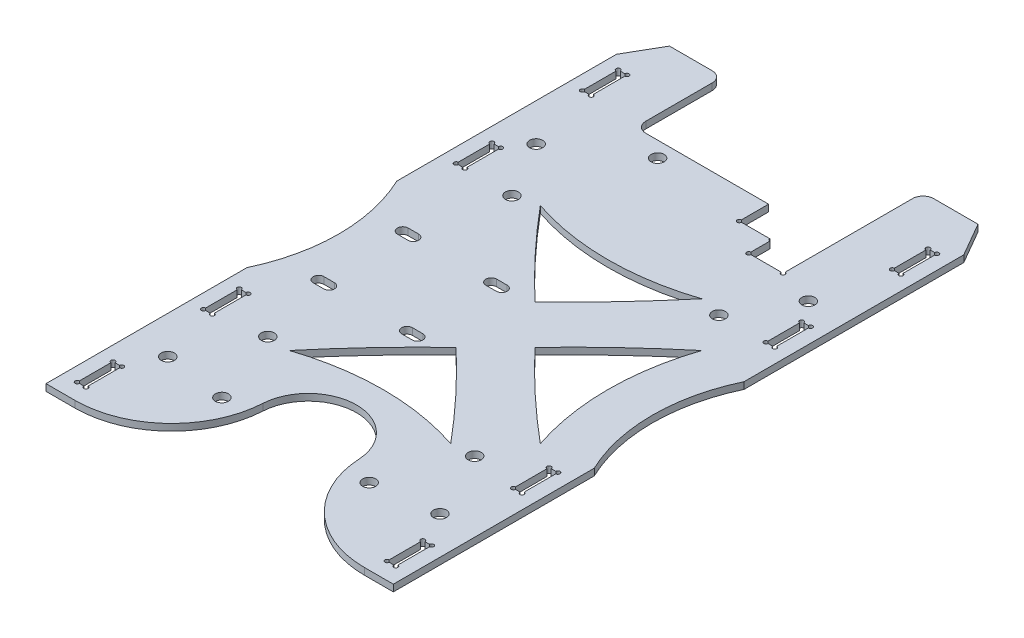
SolidWorks part; units mm, degrees
ref_plane "Front Plane" through (0, 0, 0) normal (0, 0, 1) x (1, 0, 0)
ref_plane "Top Plane" through (0, 0, 0) normal (0, 1, 0) x (1, 0, 0)
ref_plane "Right Plane" through (0, 0, 0) normal (1, 0, 0) x (0, 0, -1)
sketch "草图3" plane through (0, 0, 0) normal (0, 1, 0) x (1, 0, 0)
  line L0 (-126.4995, 10.5223) -> (116.8967, 10.5223) construction
  line L5 (15.4, 76.2723) -> (23.6, 76.2723)
  line L6 (15.4, 60.7723) -> (15.4, 76.2723)
  line L19 (15.4, 60.7723) -> (23.6, 60.7723)
  line L20 (30.4719, 92.0132) -> (48.4165, 101.8402)
  line L21 (0, 41.0059) -> (0, 98.7474) construction
  line L40 (-30.4719, 92.0132) -> (-48.4165, 101.8402)
  line L64 (15.4, 68.5223) -> (27.0301, 68.5223) construction
  line L65 (19.5, 76.2723) -> (19.5, 60.7723) construction
  line L66 (23.6, 76.2723) -> (23.6, 60.7723)
  line L69 (-39.335, 78.6574) -> (3.7462, 78.6574) construction
  line L196 (30.4719, 92.0132) -> (34.3794, 64.8038)
  line L197 (-30.4719, 92.0132) -> (-34.3794, 64.8038)
  line L198 (-61.0368, 61.6666) -> (-53.9618, 56.5263)
  circle A16 centre (19.5, 78.7223) radius 1.3
  circle A31 centre (19.5, 58.3223) radius 1.3
  circle A34 centre (17.238, 95.2857) radius 2.75
  circle A35 centre (-17.238, 95.2857) radius 2.75
  circle A65 centre (-20.5, 84.6724) radius 1.3
  circle A68 centre (-20.5, 72.6424) radius 1.3
  circle A75 centre (-60.2246, 54.2781) radius 1.55
  circle A161 centre (-36, 53.5223) radius 1.55
  circle A164 centre (36, 53.5223) radius 1.55
  arc A182 (53.9618, 56.5263) -> (34.3794, 64.8038) centre (46.6659, 66.5682) cw
  arc A183 (-53.9618, 56.5263) -> (-34.3794, 64.8038) centre (-46.6659, 66.5682) ccw
  circle A201 centre (3.8, 72.6424) radius 1.3
  circle A202 centre (3.8, 84.6724) radius 1.3
  dimension "D5" = 16.6283
  dimension "D8" = 3.2724
  dimension "D10" = 110.534
  dimension "D11" = 10.5223
  dimension "D20" = 2.6
  dimension "D12" = 24.3
  dimension "D9" = 27.2094
  dimension "D70" = 2.6
  dimension "D6" = 31.1786
  dimension "D3" = 68.135
  dimension "D14" = 58
  dimension "D17" = 15.5
  dimension "D18" = 2.45
  dimension "D19" = 8.2
  dimension "D21" = 12.03
  dimension "D43" = 43
sketch "Sketch1" plane through (0, 0, 0) normal (0, 1, 0) x (1, 0, 0)
  line L0 (-1000, 0) -> (49000, 0) construction
  line L1 (0, 0) -> (0, 100.3728) construction
  line L5 (-41.25, -55) -> (-34.3696, -55)
  line L6 (41.25, -55) -> (34.3696, -55)
  line L7 (7.65, 82.35) -> (23.6, 82.35)
  line L8 (23.6, 82.35) -> (23.6, 55.25)
  line L10 (7.65, 60.7723) -> (7.65, 82.35)
  line L11 (35.75, 77.5) -> (37.85, 77.5)
  line L12 (37.85, 77.5) -> (37.85, 69)
  line L13 (37.85, 69) -> (35.75, 69)
  line L14 (35.75, 69) -> (35.75, 77.5)
  line L15 (35.75, 39) -> (35.75, 47.5)
  line L16 (35.75, 47.5) -> (37.85, 47.5)
  line L17 (37.85, 47.5) -> (37.85, 39)
  line L18 (37.85, 39) -> (35.75, 39)
  line L19 (35.75, 9) -> (35.75, 17.5) construction
  line L20 (35.75, 17.5) -> (37.85, 17.5) construction
  line L21 (37.85, 17.5) -> (37.85, 9) construction
  line L22 (37.85, 9) -> (35.75, 9) construction
  line L35 (35.75, -51) -> (35.75, -42.5)
  line L36 (35.75, -42.5) -> (37.85, -42.5)
  line L37 (37.85, -42.5) -> (37.85, -51)
  line L38 (-41.25, -55) -> (-41.25, 0)
  line L39 (7.65, 60.7723) -> (15.4, 60.7723)
  line L40 (37.85, -51) -> (35.75, -51)
  line L42 (15.4, 55.25) -> (15.4, 60.7723)
  line L43 (-37.85, -51) -> (-37.85, -42.5)
  line L44 (-37.85, -42.5) -> (-35.75, -42.5)
  line L45 (-41.25, 0) -> (-41.25, 80.5)
  line L46 (41.25, -55) -> (41.25, 0)
  line L47 (41.25, 0) -> (41.25, 80.5)
  line L48 (-41.25, 80.5) -> (-36.6408, 88.4834)
  line L49 (-36.6408, 88.4834) -> (36.6408, 88.4834)
  line L50 (41.25, 80.5) -> (36.6408, 88.4834)
  line L51 (35.75, -21) -> (35.75, -12.5)
  line L52 (35.75, -12.5) -> (37.85, -12.5)
  line L53 (37.85, -12.5) -> (37.85, -21)
  line L54 (37.85, -21) -> (35.75, -21)
  line L55 (35.75, 69) -> (35.75, 39) construction
  line L56 (-37.85, 69) -> (-37.85, 77.5)
  line L57 (-37.85, 77.5) -> (-35.75, 77.5)
  line L58 (-35.75, 77.5) -> (-35.75, 69)
  line L59 (-35.75, 69) -> (-37.85, 69)
  line L60 (-37.85, 39) -> (-37.85, 47.5)
  line L61 (-37.85, 47.5) -> (-35.75, 47.5)
  line L62 (-35.75, 47.5) -> (-35.75, 39)
  line L63 (-35.75, 39) -> (-37.85, 39)
  line L64 (-37.85, 9) -> (-37.85, 17.5) construction
  line L65 (-37.85, 17.5) -> (-35.75, 17.5) construction
  line L66 (-35.75, 17.5) -> (-35.75, 9) construction
  line L67 (-35.75, 9) -> (-37.85, 9) construction
  line L68 (-37.85, -21) -> (-37.85, -12.5)
  line L69 (-37.85, -12.5) -> (-35.75, -12.5)
  line L70 (-35.75, -12.5) -> (-35.75, -21)
  line L71 (-35.75, -21) -> (-37.85, -21)
  line L72 (15.4, 55.25) -> (23.6, 55.25)
  line L74 (-35.75, -42.5) -> (-35.75, -51)
  line L75 (-35.75, -51) -> (-37.85, -51)
  line L79 (15.4, 60.7723) -> (23.6, 60.7723) construction
  circle A2 centre (-15, 64.0223) radius 1.55
  circle A3 centre (-17.5, -36.9777) radius 1.55
  circle A6 centre (17.5, -36.9777) radius 1.55
  arc A7 (-11.4407, -33.3184) -> (-34.3696, -55) centre (-34.3696, -32.0353) cw
  arc A8 (-11.4407, -33.3184) -> (0, -22.5) centre (0, -33.9586) cw
  arc A9 (11.4407, -33.3184) -> (34.3696, -55) centre (34.3696, -32.0353) ccw
  arc A10 (11.4407, -33.3184) -> (0, -22.5) centre (0, -33.9586) ccw
  circle A11 centre (32.325, 52.5) radius 2.75 construction
  circle A12 centre (32.325, 52.5) radius 1.55
  circle A13 centre (32.325, -35) radius 1.55
  circle A14 centre (32.325, -35) radius 2.75 construction
  circle A15 centre (-32.325, 52.5) radius 1.55
  circle A16 centre (-32.325, -35) radius 1.55
  circle A17 centre (-32.325, 52.5) radius 2.75 construction
  circle A18 centre (-32.325, -35) radius 2.75 construction
  circle A19 centre (-24.575, 39) radius 1.55
  circle A20 centre (24.575, 39) radius 1.55
  circle A21 centre (24.575, -19) radius 1.55
  circle A22 centre (-24.575, -19) radius 1.55
  point P20 (-41.25, 0)
  point P23 (0, 55)
  point P26 (41.25, 0)
  point P83 (0, 88.4834)
  dimension "D20" = 5.5
  dimension "D21" = 3.1
  dimension "D22" = 64.65
  dimension "D4" = 101
  dimension "D5" = 17.5
  dimension "D6" = 15
  dimension "D7" = 64.0223
  dimension "D8" = 120
  dimension "D9" = 55
  dimension "D10" = 2
  dimension "D11" = 5
  dimension "D12" = 2.1
  dimension "D13" = 80.5
  dimension "D14" = 82.5
  dimension "D15" = 8.5
  dimension "D16" = 77.5
  dimension "D17" = 30
  dimension "D18" = 71.5
  dimension "D19" = 22.5
  dimension "D23" = 3.425
  dimension "D24" = 52.5
  dimension "D25" = 35
  dimension "D26" = 7.65
  dimension "D27" = 23.6
  dimension "D28" = 82.35
  dimension "D30" = 7.75
  dimension "D31" = 27.1
  dimension "D32" = 49.15
  dimension "D33" = 58
  dimension "D34" = 39
extrude "主结构和连接" add sketch "Sketch1" along normal blind 1.6
sketch "外部切除点示意-1" plane through (0, 0, 0) normal (0, 1, 0) x (1, 0, 0)
  line L0 (-36.6408, 88.4834) -> (36.6408, 88.4834) construction
  line L1 (0, 0) -> (-149.6598, 0) construction
  line L2 (0, -1000) -> (0, 49000) construction
  line L3 (-41.25, 28.3195) -> (-41.2859, -7.3505)
  line L4 (41.25, 28.3195) -> (41.2859, -7.3505)
  line L5 (5.1, 88.4834) -> (5.1, 67.7334) construction
  line L6 (5.1, 67.7334) -> (7.65, 67.7334)
  line L7 (5.1, 67.7334) -> (-24, 67.7334)
  line L8 (-24, 67.7334) -> (-24, 88.4834)
  line L10 (-24, 88.4834) -> (5.1, 88.4834)
  line L11 (7.65, 60.7723) -> (7.65, 82.35) construction
  line L12 (7.65, 67.7334) -> (7.65, 82.35)
  line L13 (7.65, 82.35) -> (23.6, 82.35)
  line L14 (23.6, 82.35) -> (23.6, 88.4834)
  line L15 (23.6, 88.4834) -> (5.1, 88.4834)
  arc A0 (-41.25, 28.3195) -> (-41.2859, -7.3505) centre (-78.8424, 10.5223) cw
  circle A1 centre (3.8, 72.6424) radius 1.3 construction
  arc A3 (41.25, 28.3195) -> (41.2859, -7.3505) centre (78.8424, 10.5223) ccw
  dimension "D1" = 20.75
  dimension "D2" = 3.5
extrude "底板让位" cut sketch "外部切除点示意-1" along normal through all
sketch "电源模块接口-草图" plane through (0, 0, 0) normal (0, 1, 0) x (1, 0, 0)
  line L0 (-32.25, 18.75) -> (-4.75, 18.75) construction
  line L1 (-4.75, 18.75) -> (-4.75, -1.25) construction
  line L2 (-4.75, -1.25) -> (-32.25, -1.25) construction
  line L3 (-32.25, -1.25) -> (-32.25, 18.75) construction
  line L4 (-30.25, 18.75) -> (-27.75, 18.75) construction
  line L5 (-30.25, 20.025) -> (-27.75, 20.025)
  line L6 (-30.25, 17.475) -> (-27.75, 17.475)
  line L7 (-18.5, 18.75) -> (-18.5, -1.25) construction
  line L8 (-32.25, 8.75) -> (-4.75, 8.75) construction
  line L9 (-6.75, 18.75) -> (-9.25, 18.75) construction
  line L10 (-6.75, 20.025) -> (-9.25, 20.025)
  line L11 (-6.75, 17.475) -> (-9.25, 17.475)
  line L12 (-30.25, -1.25) -> (-27.75, -1.25) construction
  line L13 (-30.25, -2.525) -> (-27.75, -2.525)
  line L14 (-30.25, 0.025) -> (-27.75, 0.025)
  line L15 (-6.75, -1.25) -> (-9.25, -1.25) construction
  line L16 (-6.75, -2.525) -> (-9.25, -2.525)
  line L17 (-6.75, 0.025) -> (-9.25, 0.025)
  arc A0 (-30.25, 20.025) -> (-30.25, 17.475) centre (-30.25, 18.75) ccw
  arc A1 (-27.75, 17.475) -> (-27.75, 20.025) centre (-27.75, 18.75) ccw
  arc A2 (-6.75, 20.025) -> (-6.75, 17.475) centre (-6.75, 18.75) cw
  arc A3 (-9.25, 17.475) -> (-9.25, 20.025) centre (-9.25, 18.75) cw
  arc A4 (-30.25, -2.525) -> (-30.25, 0.025) centre (-30.25, -1.25) cw
  arc A5 (-27.75, 0.025) -> (-27.75, -2.525) centre (-27.75, -1.25) cw
  arc A6 (-6.75, -2.525) -> (-6.75, 0.025) centre (-6.75, -1.25) ccw
  arc A7 (-9.25, 0.025) -> (-9.25, -2.525) centre (-9.25, -1.25) ccw
  point P6 (-29, 18.75)
  point P17 (-8, 18.75)
  point P24 (-29, -1.25)
  point P31 (-8, -1.25)
  dimension "D3" = 1.275
  dimension "D1" = 27.5
  dimension "D2" = 20
  dimension "D4" = 2.5
  dimension "D5" = 10.5
  dimension "D6" = 18.5
  dimension "D7" = 8.75
extrude "电源模块接口" cut sketch "电源模块接口-草图" along normal through all
sketch "草图2" plane through (0, 1.6, 0) normal (0, 1, 0) x (1, 0, 0)
  line L0 (0, 0) -> (0, 53.6886) construction
  line L1 (0, 0) -> (0, 100.3728) construction
  line L2 (0, 0) -> (139.6377, 0) construction
  line L3 (-201000, 0) -> (249000, 0) construction
  line L4 (0, 19.8942) -> (0, 10.5223) construction
  line L5 (0, 10.5223) -> (9.3719, 10.5223) construction
  arc A3 (9.3719, 10.5223) -> (29.8202, 29.7013) centre (187.9553, -159.3904) cw
  arc A4 (29.8202, 29.7013) -> (29.8202, -8.6566) centre (87.1283, 10.5223) ccw
  arc A5 (29.8202, -8.6566) -> (9.3719, 10.5223) centre (187.9553, 180.4351) cw
  circle A6 centre (0, 10.5223) radius 9.3719 construction
  arc A7 (0, 1.1505) -> (19.1789, -19.2978) centre (-169.9128, -177.433) cw
  arc A8 (19.1789, -19.2978) -> (-19.1789, -19.2978) centre (0, -76.6059) ccw
  arc A9 (-19.1789, -19.2978) -> (0, 1.1505) centre (169.9128, -177.433) cw
  arc A10 (-9.3719, 10.5223) -> (-29.8202, -8.6566) centre (-187.9553, 180.4351) cw construction
  arc A11 (-29.8202, -8.6566) -> (-29.8202, 29.7013) centre (-87.1283, 10.5223) ccw construction
  arc A12 (-29.8202, 29.7013) -> (-9.3719, 10.5223) centre (-187.9553, -159.3904) cw construction
  arc A13 (0, 19.8942) -> (-19.1789, 40.3425) centre (169.9128, 198.4777) cw
  arc A14 (-19.1789, 40.3425) -> (19.1789, 40.3425) centre (0, 97.6506) ccw
  arc A15 (19.1789, 40.3425) -> (0, 19.8942) centre (-169.9128, 198.4777) cw
  point P38 (0, 10.5223)
  dimension "D1" = 10.5223
  dimension "D2" = 4
extrude "飞控走线" cut sketch "草图2" against normal blind 10
fillet "圆角1" radius 2.5 3 edges at (-24, 0.8, -67.7334) (-24, 0.8, -88.4834) (23.6, 0.8, -88.4834)
sketch "刀口-草图" plane through (0, 0, 0) normal (0, 1, 0) x (1, 0, 0)
  line L0 (0, 0) -> (0, 127.8448) construction
  circle A0 centre (7.65, 60.7723) radius 0.5
  circle A1 centre (15.4, 60.7723) radius 0.5
  circle A2 centre (15.4, 55.25) radius 0.5
  circle A3 centre (23.6, 55.25) radius 0.5
  circle A4 centre (35.75, 69) radius 0.5
  circle A5 centre (37.85, 69) radius 0.5
  circle A6 centre (35.75, 77.5) radius 0.5
  circle A7 centre (37.85, 77.5) radius 0.5
  circle A8 centre (35.75, 47.5) radius 0.5
  circle A9 centre (37.85, 47.5) radius 0.5
  circle A10 centre (35.75, 39) radius 0.5
  circle A11 centre (37.85, 39) radius 0.5
  circle A12 centre (35.75, -12.5) radius 0.5
  circle A13 centre (37.85, -12.5) radius 0.5
  circle A14 centre (35.75, -21) radius 0.5
  circle A15 centre (37.85, -21) radius 0.5
  circle A16 centre (35.75, -42.5) radius 0.5
  circle A17 centre (37.85, -42.5) radius 0.5
  circle A18 centre (35.75, -51) radius 0.5
  circle A19 centre (37.85, -51) radius 0.5
  circle A20 centre (-37.85, -51) radius 0.5
  circle A21 centre (-35.75, -51) radius 0.5
  circle A22 centre (-37.85, -42.5) radius 0.5
  circle A23 centre (-35.75, -42.5) radius 0.5
  circle A24 centre (-37.85, -21) radius 0.5
  circle A25 centre (-35.75, -21) radius 0.5
  circle A26 centre (-37.85, -12.5) radius 0.5
  circle A27 centre (-35.75, -12.5) radius 0.5
  circle A28 centre (-37.85, 39) radius 0.5
  circle A29 centre (-35.75, 39) radius 0.5
  circle A30 centre (-37.85, 47.5) radius 0.5
  circle A31 centre (-35.75, 47.5) radius 0.5
  circle A32 centre (-37.85, 77.5) radius 0.5
  circle A33 centre (-35.75, 77.5) radius 0.5
  circle A34 centre (-37.85, 69) radius 0.5
  circle A35 centre (-35.75, 69) radius 0.5
  dimension "D1" = 1
extrude "刀口" cut sketch "刀口-草图" along normal through all
